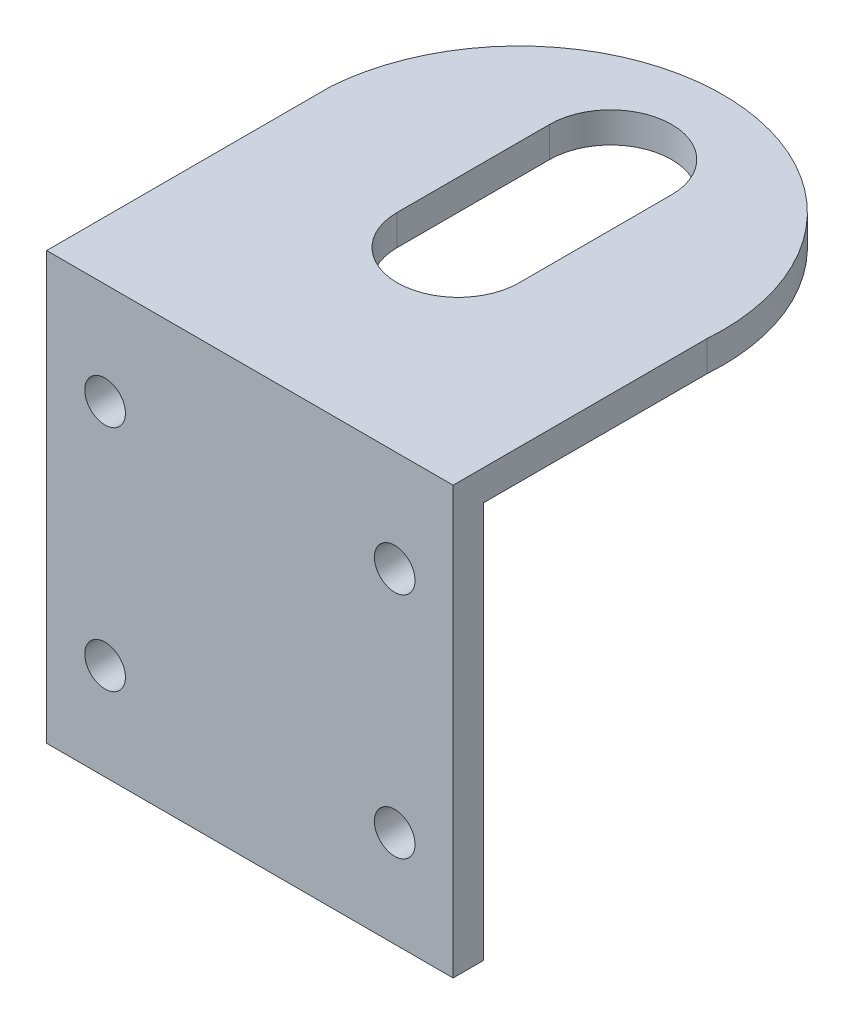
SolidWorks part; units mm, degrees
ref_plane "前视" through (0, 0, 0) normal (0, 0, 1) x (1, 0, 0)
ref_plane "上视" through (0, 0, 0) normal (0, 1, 0) x (1, 0, 0)
ref_plane "右视" through (0, 0, 0) normal (1, 0, 0) x (0, 0, -1)
sketch "Sketch1" plane through (0, 0, 0) normal (0, 1, 0) x (1, 0, 0)
  line L0 (20, 35.5) -> (20, 20.5) construction
  line L1 (0, 0) -> (40, 0)
  line L2 (0, 0) -> (0, 28)
  line L3 (26, 35.5) -> (26, 20.5)
  line L4 (40, 0) -> (40, 25)
  line L5 (14, 35.5) -> (14, 20.5)
  arc A0 (40, 25) -> (0, 28) centre (20, 26.5) ccw
  arc A1 (26, 35.5) -> (14, 35.5) centre (20, 35.5) ccw
  arc A2 (14, 20.5) -> (26, 20.5) centre (20, 20.5) ccw
  point P8 (20, 28)
  dimension "D1" = 40
  dimension "D2" = 28
  dimension "D3" = 15
  dimension "D4" = 0
extrude "Extrude2" add sketch "Sketch1" along normal blind 3
sketch "Sketch3" plane through (0, 0, 0) normal (0, -1, 0) x (1, 0, 0)
  line L0 (0, -28) -> (0, 0) construction
  line L1 (40, 0) -> (0, 0)
  line L2 (40, 0) -> (40, -3)
  line L3 (40, -3) -> (0, -3)
  line L4 (0, 0) -> (0, -3)
  dimension "D1" = 3
extrude "Extrude3" add sketch "Sketch3" along normal blind 39
sketch "Sketch4" plane through (0, 0, 0) normal (0, 0, 1) x (1, 0, 0)
  line L0 (0, 3) -> (40, 3) construction
  line L1 (40, 3) -> (40, -39) construction
  circle A0 centre (34.25, -7) radius 2
  circle A1 centre (5.75, -7) radius 2
  circle A2 centre (5.75, -29.5) radius 2
  circle A3 centre (34.25, -29.5) radius 2
  dimension "D1" = 10
  dimension "D2" = 5.75
  dimension "D3" = 2
  dimension "D4" = 2
extrude "Extrude4" cut sketch "Sketch4" against normal through all
